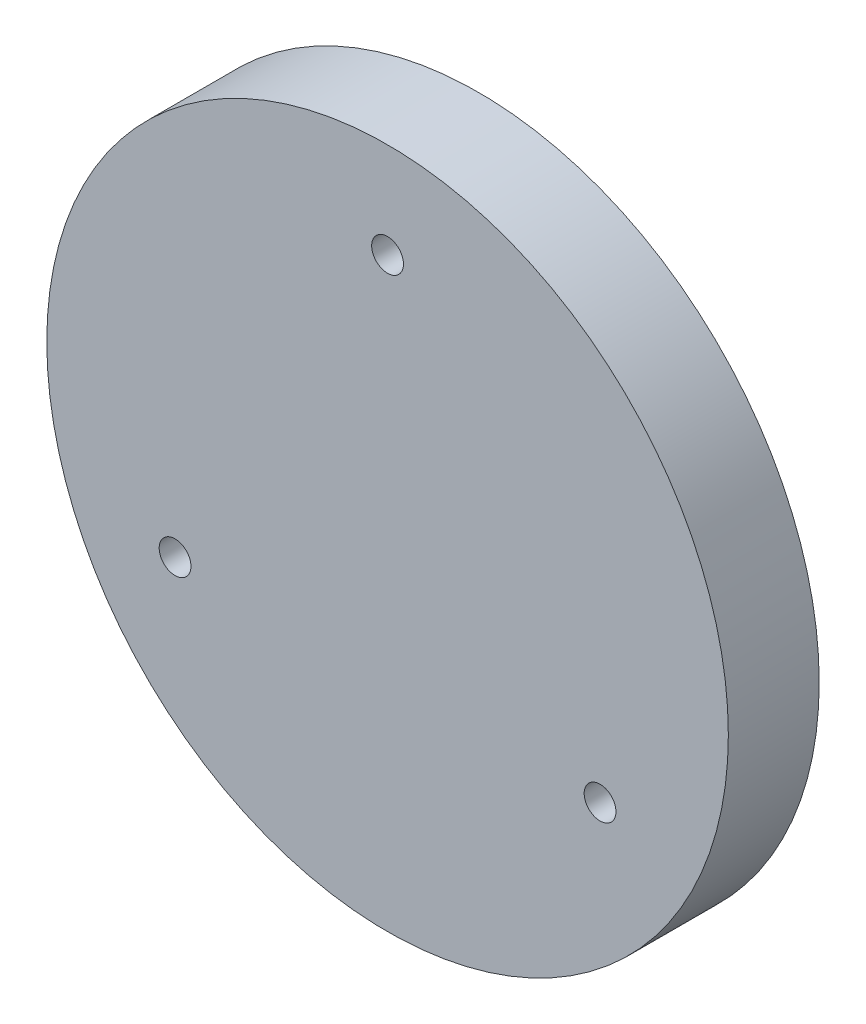
SolidWorks part; units mm, degrees
ref_plane "Front Plane" through (0, 0, 0) normal (0, 0, 1) x (1, 0, 0)
ref_plane "Top Plane" through (0, 0, 0) normal (0, 1, 0) x (1, 0, 0)
ref_plane "Right Plane" through (0, 0, 0) normal (1, 0, 0) x (0, 0, -1)
sketch "Sketch1" plane through (0, 0, 0) normal (0, 0, 1) x (1, 0, 0)
  circle A0 centre (0, 0) radius 27 construction
  circle A1 centre (0, 0) radius 37.5
  circle A2 centre (0, 27) radius 1.75
  circle A3 centre (23.3827, -13.5) radius 1.75
  circle A4 centre (-23.3827, -13.5) radius 1.75
  point P13 (0, 0)
  dimension "D1" = 54
  dimension "D2" = 75
  dimension "D3" = 3.5
  dimension "D4" = 3
extrude "Boss-Extrude1" add sketch "Sketch1" along normal blind 10
